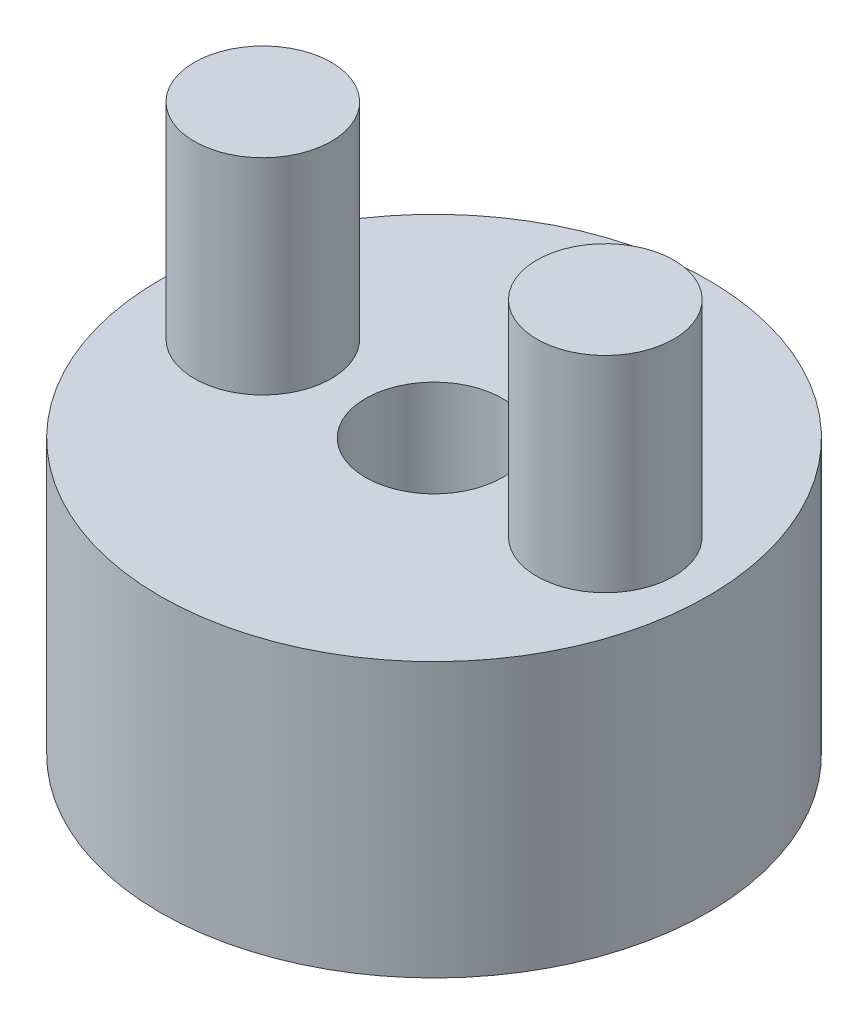
SolidWorks part; units mm, degrees
material "6061 Alloy"
ref_plane "Front Plane" through (0, 0, 0) normal (0, 0, 1) x (1, 0, 0)
ref_plane "Top Plane" through (0, 0, 0) normal (0, 1, 0) x (1, 0, 0)
ref_plane "Right Plane" through (0, 0, 0) normal (1, 0, 0) x (0, 0, -1)
sketch "Sketch1" plane through (0, 0, 0) normal (0, 1, 0) x (1, 0, 0)
  circle A0 centre (0, 0) radius 6.35
extrude "Boss-Extrude1" add sketch "Sketch1" along normal blind 6.35
hole_wizard "1/8 (0.125) Diameter Hole1" positions "Sketch2" profile "Sketch3" hole size "1/8" standard "ANSI Inch" end condition through all
sketch "Sketch2" plane through (0, 6.35, 0) normal (0, 1, 0) x (1, 0, 0)
  point P0 (0, 0)
sketch "Sketch3" plane through (0, 6.35, 0) normal (1, 0, 0) x (0, 0, 1)
  line L0 (0, 0) -> (0, 6.35)
  line L1 (0, 6.35) -> (1.5875, 6.35)
  line L2 (1.5875, 6.35) -> (1.5875, 0)
  line L5 (1.5875, 0) -> (0, 0)
  line L11 (0, -6.35) -> (0, 107.95) construction
  dimension "Thru Hole Dia." = 3.175
  dimension "Thru Hole Depth" = 6.35
sketch "Sketch4" plane through (0, 6.35, 0) normal (0, 1, 0) x (1, 0, 0)
  circle A0 centre (3.9688, 0) radius 1.5875
  circle A1 centre (-3.9688, 0) radius 1.5875
  circle A2 centre (0, 0) radius 1.5875 construction
  dimension "D3" = 3.175
  dimension "D4" = 3.175
  dimension "D1" = 3.9688
  dimension "D2" = 3.9688
extrude "Boss-Extrude2" add sketch "Sketch4" along normal blind 4.7625
